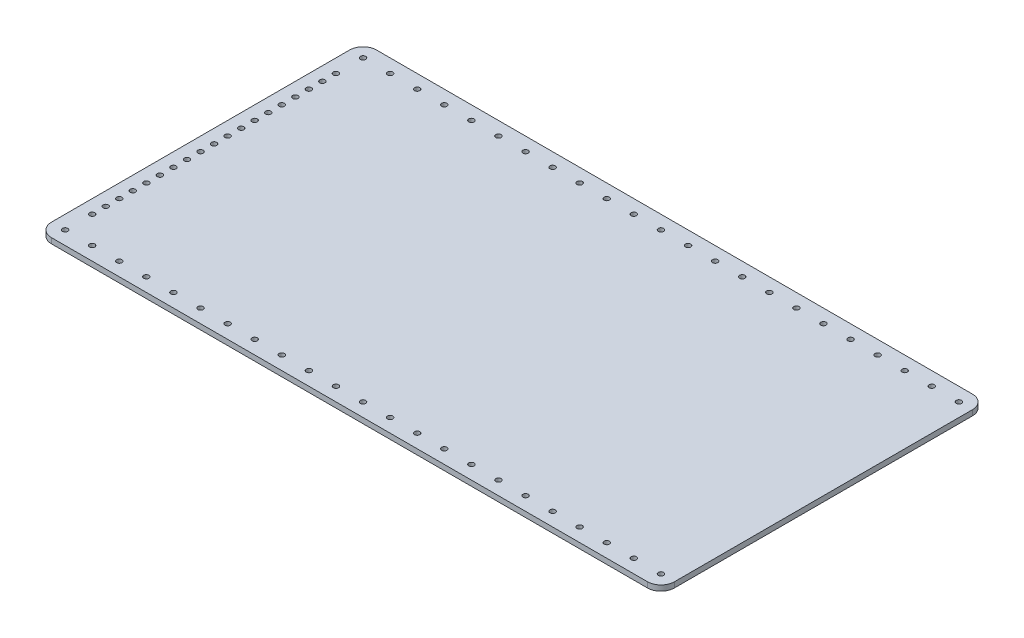
SolidWorks part; units mm, degrees
material "PC High Viscosity"
ref_plane "Front Plane" through (0, 0, 0) normal (0, 0, 1) x (1, 0, 0)
ref_plane "Top Plane" through (0, 0, 0) normal (0, 1, 0) x (1, 0, 0)
ref_plane "Right Plane" through (0, 0, 0) normal (1, 0, 0) x (0, 0, -1)
sketch "Sketch1" plane through (0, 0, 0) normal (0, 1, 0) x (1, 0, 0)
  line L1 (0, 0) -> (584.2, 0)
  line L2 (0, 0) -> (0, 304.8)
  line L3 (0, 304.8) -> (584.2, 304.8)
  line L4 (584.2, 0) -> (584.2, 304.8)
  dimension "D1" = 584.2
  dimension "D2" = 304.8
extrude "Boss-Extrude1" add sketch "Sketch1" along normal blind 5.08
sketch "Sketch2" plane through (0, 5.08, 0) normal (0, 1, 0) x (1, 0, 0)
  line L1 (50.8, 241.3) -> (228.6, 241.3)
  line L2 (50.8, 241.3) -> (50.8, 63.5)
  line L3 (50.8, 63.5) -> (228.6, 63.5)
  line L4 (228.6, 241.3) -> (228.6, 63.5)
  line L6 (584.2, 304.8) -> (0, 304.8) construction
  line L7 (0, 304.8) -> (0, 0) construction
  line L9 (254, 241.3) -> (431.8, 241.3)
  line L10 (254, 241.3) -> (254, 63.5)
  line L11 (254, 63.5) -> (431.8, 63.5)
  line L12 (431.8, 241.3) -> (431.8, 63.5)
  dimension "D1" = 177.8
  dimension "D2" = 177.8
  dimension "D3" = 63.5
  dimension "D4" = 50.8
  dimension "D5" = 177.8
  dimension "D6" = 177.8
  dimension "D7" = 25.4
  dimension "D8" = 63.5
sketch "Sketch3" plane through (0, 5.08, 0) normal (0, 1, 0) x (1, 0, 0)
  line L0 (584.2, 304.8) -> (0, 304.8) construction
  line L1 (0, 304.8) -> (0, 0) construction
  line L2 (12.7, 292.1) -> (38.1, 292.1) construction
  line L3 (12.7, 292.1) -> (12.7, 266.7) construction
  line L4 (12.7, 12.7) -> (38.1, 12.7) construction
  line L5 (12.7, 254) -> (12.7, 228.6) construction
  circle A0 centre (12.7, 292.1) radius 2.4892
  circle A1 centre (38.1, 292.1) radius 2.4892
  circle A2 centre (63.5, 292.1) radius 2.4892
  circle A3 centre (88.9, 292.1) radius 2.4892
  circle A4 centre (114.3, 292.1) radius 2.4892
  circle A5 centre (139.7, 292.1) radius 2.4892
  circle A6 centre (165.1, 292.1) radius 2.4892
  circle A7 centre (190.5, 292.1) radius 2.4892
  circle A8 centre (215.9, 292.1) radius 2.4892
  circle A9 centre (241.3, 292.1) radius 2.4892
  circle A10 centre (266.7, 292.1) radius 2.4892
  circle A11 centre (292.1, 292.1) radius 2.4892
  circle A12 centre (317.5, 292.1) radius 2.4892
  circle A13 centre (342.9, 292.1) radius 2.4892
  circle A14 centre (368.3, 292.1) radius 2.4892
  circle A15 centre (393.7, 292.1) radius 2.4892
  circle A16 centre (419.1, 292.1) radius 2.4892
  circle A17 centre (444.5, 292.1) radius 2.4892
  circle A18 centre (469.9, 292.1) radius 2.4892
  circle A19 centre (495.3, 292.1) radius 2.4892
  circle A20 centre (520.7, 292.1) radius 2.4892
  circle A21 centre (546.1, 292.1) radius 2.4892
  circle A22 centre (571.5, 292.1) radius 2.4892
  circle A23 centre (12.7, 266.7) radius 2.4892
  circle A24 centre (12.7, 241.3) radius 2.4892
  circle A25 centre (12.7, 215.9) radius 2.4892
  circle A26 centre (12.7, 190.5) radius 2.4892
  circle A27 centre (12.7, 165.1) radius 2.4892
  circle A28 centre (12.7, 139.7) radius 2.4892
  circle A29 centre (12.7, 114.3) radius 2.4892
  circle A30 centre (12.7, 88.9) radius 2.4892
  circle A31 centre (12.7, 63.5) radius 2.4892
  circle A32 centre (12.7, 38.1) radius 2.4892
  circle A33 centre (12.7, 12.7) radius 2.4892
  circle A34 centre (38.1, 12.7) radius 2.4892
  circle A35 centre (63.5, 12.7) radius 2.4892
  circle A36 centre (88.9, 12.7) radius 2.4892
  circle A37 centre (114.3, 12.7) radius 2.4892
  circle A38 centre (139.7, 12.7) radius 2.4892
  circle A39 centre (165.1, 12.7) radius 2.4892
  circle A40 centre (190.5, 12.7) radius 2.4892
  circle A41 centre (215.9, 12.7) radius 2.4892
  circle A42 centre (241.3, 12.7) radius 2.4892
  circle A43 centre (266.7, 12.7) radius 2.4892
  circle A44 centre (292.1, 12.7) radius 2.4892
  circle A45 centre (317.5, 12.7) radius 2.4892
  circle A46 centre (342.9, 12.7) radius 2.4892
  circle A47 centre (368.3, 12.7) radius 2.4892
  circle A48 centre (393.7, 12.7) radius 2.4892
  circle A49 centre (419.1, 12.7) radius 2.4892
  circle A50 centre (444.5, 12.7) radius 2.4892
  circle A51 centre (469.9, 12.7) radius 2.4892
  circle A52 centre (495.3, 12.7) radius 2.4892
  circle A53 centre (520.7, 12.7) radius 2.4892
  circle A54 centre (546.1, 12.7) radius 2.4892
  circle A55 centre (571.5, 12.7) radius 2.4892
  circle A56 centre (12.7, 254) radius 2.4892
  circle A57 centre (12.7, 228.6) radius 2.4892
  circle A58 centre (12.7, 203.2) radius 2.4892
  circle A59 centre (12.7, 177.8) radius 2.4892
  circle A60 centre (12.7, 152.4) radius 2.4892
  circle A61 centre (12.7, 127) radius 2.4892
  circle A62 centre (12.7, 101.6) radius 2.4892
  circle A63 centre (12.7, 76.2) radius 2.4892
  circle A64 centre (12.7, 50.8) radius 2.4892
  dimension "D1" = 12.7
  dimension "D2" = 4.9784
  dimension "D3" = 12.7
  dimension "D10" = 12.7
  dimension "D5" = 25.4
  dimension "D7" = 25.4
  dimension "D9" = 25.4
  dimension "D12" = 25.4
  dimension "D4" = 23
  dimension "D6" = 12
  dimension "D8" = 23
  dimension "D11" = 9
extrude "Cut-Extrude1" cut sketch "Sketch3" against normal through all
fillet "Fillet1" radius 12.7 4 edges at (584.2, 2.54, -304.8) (584.2, 2.54, 0) (0, 2.54, 0) (0, 2.54, -304.8)
